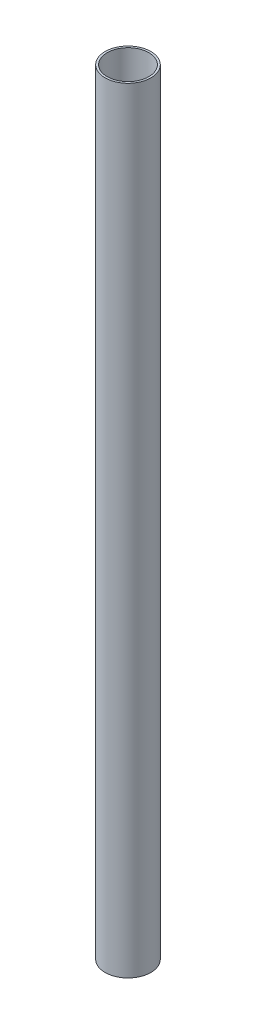
SolidWorks part; units mm, degrees
ref_plane "Front Plane" through (0, 0, 0) normal (0, 0, 1) x (1, 0, 0)
ref_plane "Top Plane" through (0, 0, 0) normal (0, 1, 0) x (1, 0, 0)
ref_plane "Right Plane" through (0, 0, 0) normal (1, 0, 0) x (0, 0, -1)
sketch "Sketch1" plane through (0, 0, 0) normal (0, 1, 0) x (1, 0, 0)
  circle A0 centre (0, 0) radius 13.6525
  circle A1 centre (0, 0) radius 14.986
  dimension "D1" = 29.972
  dimension "D2" = 27.305
extrude "Boss-Extrude1" add sketch "Sketch1" along normal blind 508
